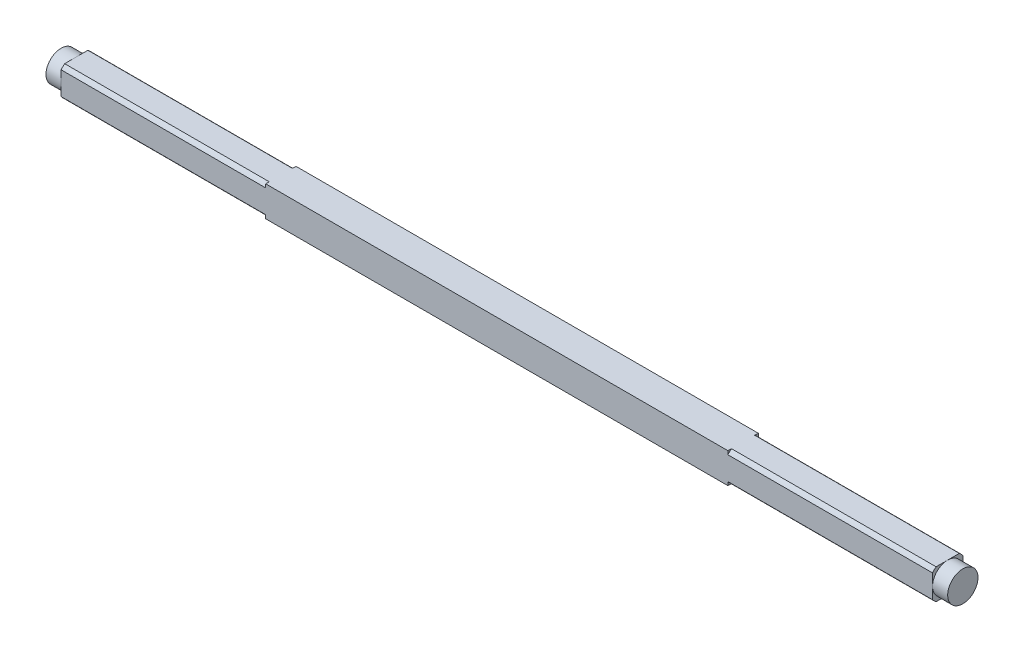
SolidWorks part; units mm, degrees
ref_plane "Front Plane" through (0, 0, 0) normal (0, 0, 1) x (1, 0, 0)
ref_plane "Top Plane" through (0, 0, 0) normal (0, 1, 0) x (1, 0, 0)
ref_plane "Right Plane" through (0, 0, 0) normal (1, 0, 0) x (0, 0, -1)
sketch "Sketch1" plane through (0, 0, 0) normal (1, 0, 0) x (0, 0, -1)
  line L1 (3.175, -3.175) -> (-3.175, -3.175)
  line L2 (3.175, -3.175) -> (3.175, 3.175)
  line L3 (3.175, 3.175) -> (-3.175, 3.175)
  line L4 (-3.175, -3.175) -> (-3.175, 3.175)
  line L5 (3.175, -3.175) -> (-3.175, 3.175) construction
  line L6 (3.175, 3.175) -> (-3.175, -3.175) construction
  point P0 (0, 0)
  dimension "D1" = 6.35
extrude "Boss-Extrude1" add sketch "Sketch1" along normal blind 94.4562
sketch "Sketch2" plane through (94.4562, 0, 0) normal (1, 0, 0) x (0, 0, -1)
  line L0 (3.175, 3.175) -> (-3.175, 3.175) construction
  line L2 (3.9688, -3.9688) -> (-3.9688, -3.9688)
  line L3 (3.9688, -3.9688) -> (3.9688, 3.9688)
  line L4 (3.9688, 3.9688) -> (-3.9688, 3.9687)
  line L5 (-3.9688, -3.9688) -> (-3.9688, 3.9687)
  line L6 (3.9688, -3.9688) -> (-3.9688, 3.9687) construction
  line L7 (3.9688, 3.9688) -> (-3.9688, -3.9688) construction
  circle A0 centre (0, 0) radius 3.175
  dimension "D1" = 7.9375
extrude "Cut-Extrude1" cut sketch "Sketch2" against normal blind 3.175
sketch "Sketch3" plane through (91.2812, 0, 0) normal (1, 0, 0) x (0, 0, -1)
  line L0 (-3.175, 0) -> (-3.175, -3.175) construction
  line L1 (-3.175, -3.175) -> (0, -3.175) construction
  line L2 (0, -3.175) -> (3.175, -3.175) construction
  line L3 (3.175, -3.175) -> (3.175, 0) construction
  line L4 (3.175, 0) -> (3.175, 3.175) construction
  line L5 (3.175, 3.175) -> (0, 3.175) construction
  line L6 (-3.175, 3.175) -> (-3.175, 0) construction
  line L7 (0, 3.175) -> (-3.175, 3.175) construction
  line L8 (-3.175, -2.433) -> (-3.175, -3.175)
  line L9 (-3.175, -3.175) -> (-2.433, -3.175)
  line L10 (2.433, -3.175) -> (3.175, -3.175)
  line L11 (3.175, -3.175) -> (3.175, -2.433)
  line L12 (3.175, 2.433) -> (3.175, 3.175)
  line L13 (3.175, 3.175) -> (2.433, 3.175)
  line L14 (-3.175, 3.175) -> (-3.175, 2.433)
  line L15 (-2.433, 3.175) -> (-3.175, 3.175)
  arc A0 (3.175, 2.433) -> (2.433, 3.175) centre (0, 0) ccw
  arc A5 (-2.433, 3.175) -> (-3.175, 2.433) centre (0, 0) ccw
  arc A6 (-3.175, -2.433) -> (-2.433, -3.175) centre (0, 0) ccw
  arc A7 (2.433, -3.175) -> (3.175, -2.433) centre (0, 0) ccw
  point P18 (-3.175, 2.364)
  point P19 (0, 0)
  dimension "D1" = 8
extrude "Cut-Extrude2" cut sketch "Sketch3" against normal blind 42.8625
mirror "Mirror1" about plane through (0, 0, 0) normal (1, 0, 0) of bodies 104 102
